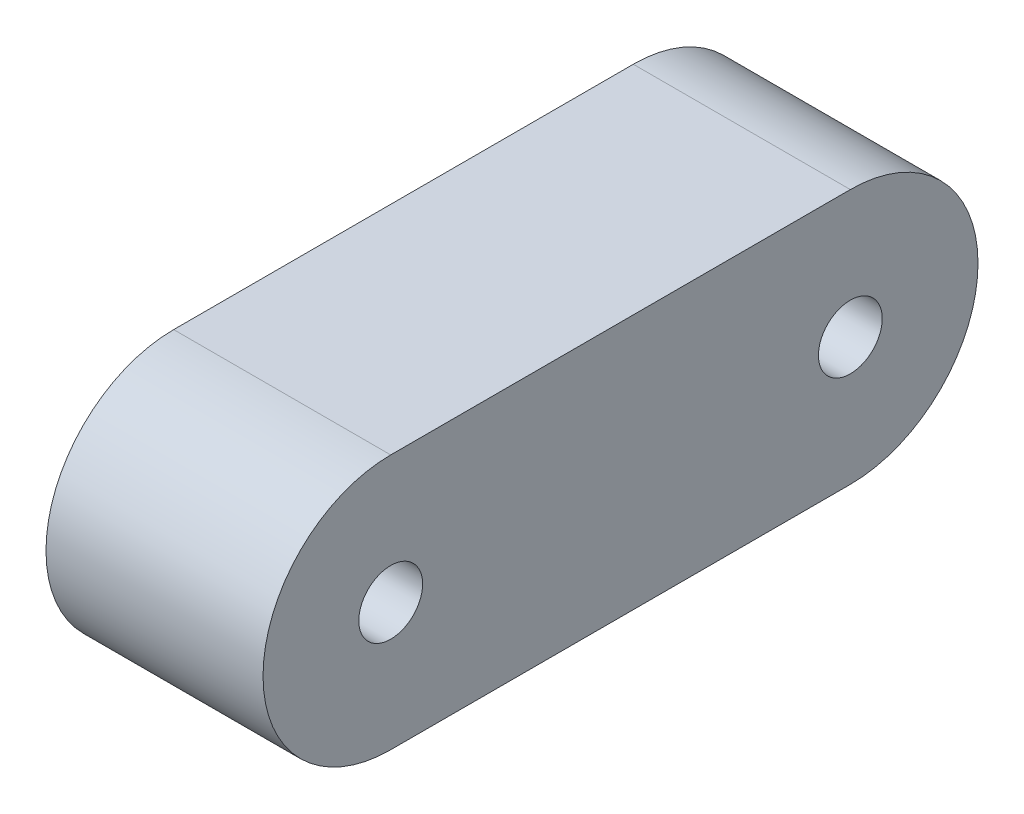
SolidWorks part; units mm, degrees
ref_plane "Alzado" through (0, 0, 0) normal (0, 0, 1) x (1, 0, 0)
ref_plane "Planta" through (0, 0, 0) normal (0, 1, 0) x (1, 0, 0)
ref_plane "Vista lateral" through (0, 0, 0) normal (1, 0, 0) x (0, 0, -1)
sketch "Croquis1" plane through (0, 0, 0) normal (1, 0, 0) x (0, 0, -1)
  line L0 (-18, 0) -> (18, 0) construction
  line L1 (-18, 10) -> (18, 10)
  line L2 (-18, -10) -> (18, -10)
  arc A0 (-18, 10) -> (-18, -10) centre (-18, 0) ccw
  arc A1 (18, -10) -> (18, 10) centre (18, 0) ccw
  circle A2 centre (-18, 0) radius 2.5
  circle A3 centre (18, 0) radius 2.5
  point P4 (0, 0)
  dimension "D1" = 20
  dimension "D3" = 5
  dimension "D2" = 36
extrude "Saliente-Extruir1" add sketch "Croquis1" along normal mid plane 17
